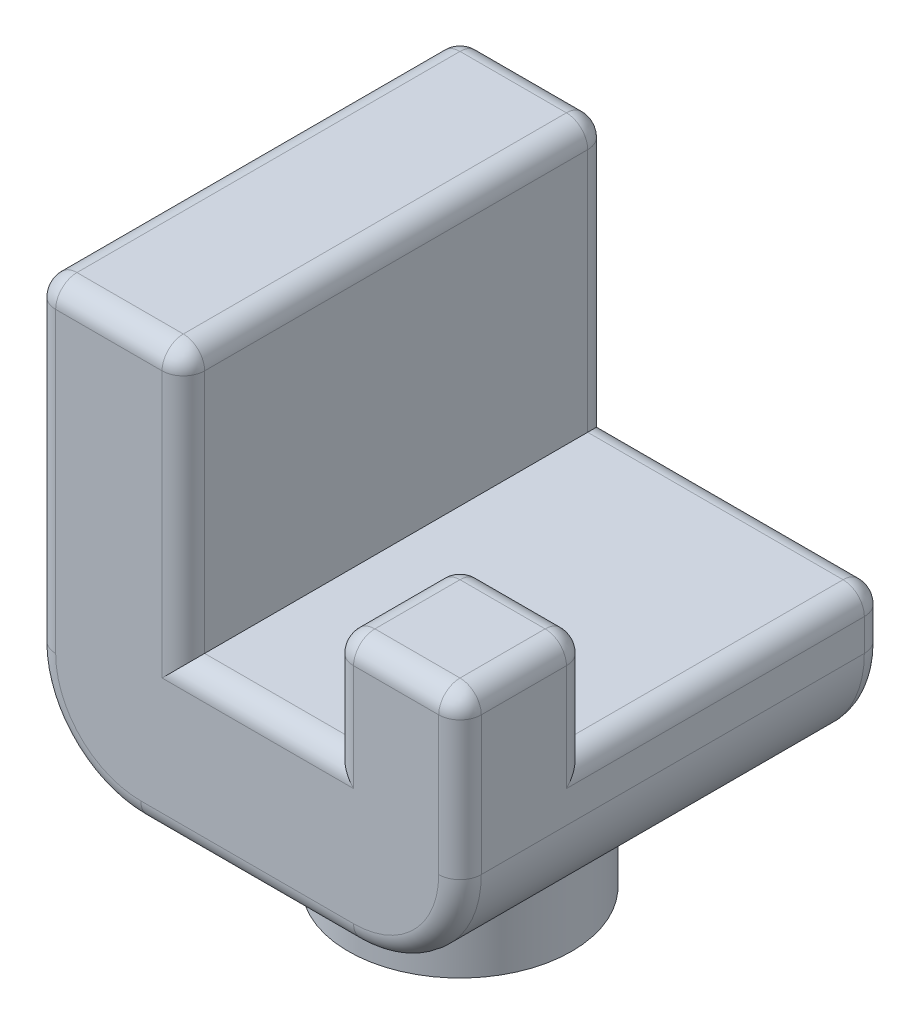
SolidWorks part; units mm, degrees
ref_plane "Front Plane" through (0, 0, 0) normal (0, 0, 1) x (1, 0, 0)
ref_plane "Top Plane" through (0, 0, 0) normal (0, 1, 0) x (1, 0, 0)
ref_plane "Right Plane" through (0, 0, 0) normal (1, 0, 0) x (0, 0, -1)
sketch "Sketch1" plane through (0, 0, 0) normal (0, 0, 1) x (1, 0, 0)
  line L1 (-10, 10) -> (10, 10)
  line L2 (-10, 10) -> (-10, -10)
  line L3 (-10, -10) -> (10, -10)
  line L4 (10, 10) -> (10, -10)
  line L5 (-10, 10) -> (10, -10) construction
  line L6 (-10, -10) -> (10, 10) construction
  point P0 (0, 0)
extrude "Boss-Extrude1" add sketch "Sketch1" along normal blind 20
sketch "Sketch2" plane through (0, 0, 20) normal (0, 0, 1) x (1, 0, 0)
  line L2 (10, -10) -> (10, 10) construction
  line L3 (4, 2.5) -> (4, -2.5)
  line L5 (10, 2.5) -> (4, 2.5)
  line L6 (4, -2.5) -> (-3, -2.5)
  line L7 (-3, -2.5) -> (-3, 10)
  line L8 (10, 10) -> (-10, 10) construction
  line L9 (-3, 10) -> (10, 10)
  line L10 (10, 10) -> (10, 2.5)
extrude "Cut-Extrude1" cut sketch "Sketch2" against normal blind 25
sketch "Sketch3" plane through (10, 0, 0) normal (1, 0, 0) x (0, 0, -1)
  line L1 (0, 2.5) -> (-14, 2.5)
  line L2 (0, 2.5) -> (0, -2.5)
  line L3 (0, -2.5) -> (-14, -2.5)
  line L4 (-14, 2.5) -> (-14, -2.5)
extrude "Cut-Extrude2" cut sketch "Sketch3" against normal up to surface (13 mm away) up to face at (-3, 3.75, 10)
fillet "Fillet1" radius 5 2 edges at (10, -10, 10) (-10, -10, 10)
fillet "Fillet2" radius 1 15 edges at (-8.5355, -8.5355, 0) (0, -10, 0) (8.5355, -8.5355, 0) (8.5355, -8.5355, 20) (0, -10, 20) (-8.5355, -8.5355, 20) (-10, 2.5, 0) (-3, 3.75, 0) (4, 0, 14) (10, -3.75, 0) (10, 0, 14) (10, -1.25, 20) (4, 0, 20) (-3, 3.75, 20) (-10, 2.5, 20)
fillet "Fillet3" radius 1 20 edges at (2.5, -2.5, 0) (9.7071, -2.5, 0.2929) (10, -2.5, 8) (9.7071, 2.5, 19.7071) (10, 2.5, 17) (9.7071, 2.5, 14.2929) (7, 2.5, 14) (4.2929, 2.5, 14.2929) (4, 2.5, 17) (4.2929, 2.5, 19.7071) (7, 2.5, 20) (0.5, -2.5, 20) (-3.2929, 10, 0.2929) (-9.7071, 10, 0.2929) (-6.5, 10, 0) (-3, 10, 10) (-3.2929, 10, 19.7071) (-9.7071, 10, 19.7071) (-6.5, 10, 20) (-10, 10, 10)
sketch "Sketch4" plane through (0, -10, 0) normal (0, -1, 0) x (1, 0, 0)
  circle A0 centre (0, 10) radius 5.25
extrude "Boss-Extrude2" add sketch "Sketch4" along normal blind 5
